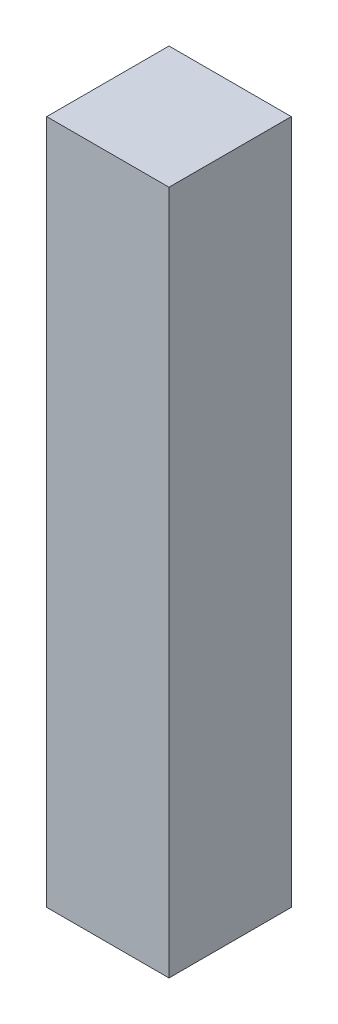
SolidWorks part; units mm, degrees
ref_plane "前视基准面" through (0, 0, 0) normal (0, 0, 1) x (1, 0, 0)
ref_plane "上视基准面" through (0, 0, 0) normal (0, 1, 0) x (1, 0, 0)
ref_plane "右视基准面" through (0, 0, 0) normal (1, 0, 0) x (0, 0, -1)
other "Configuration Table"
sketch "草图1" plane through (0, 0, 0) normal (0, 0, 1) x (1, 0, 0)
  line L0 (0, 0) -> (5, 0)
  line L1 (5, 0) -> (5, 28)
  line L2 (5, 28) -> (0, 28)
  line L3 (0, 28) -> (0, 0)
  dimension "width" = 5
  dimension "height" = 28
extrude "Guide_side_brace" add sketch "草图1" along normal blind 5
